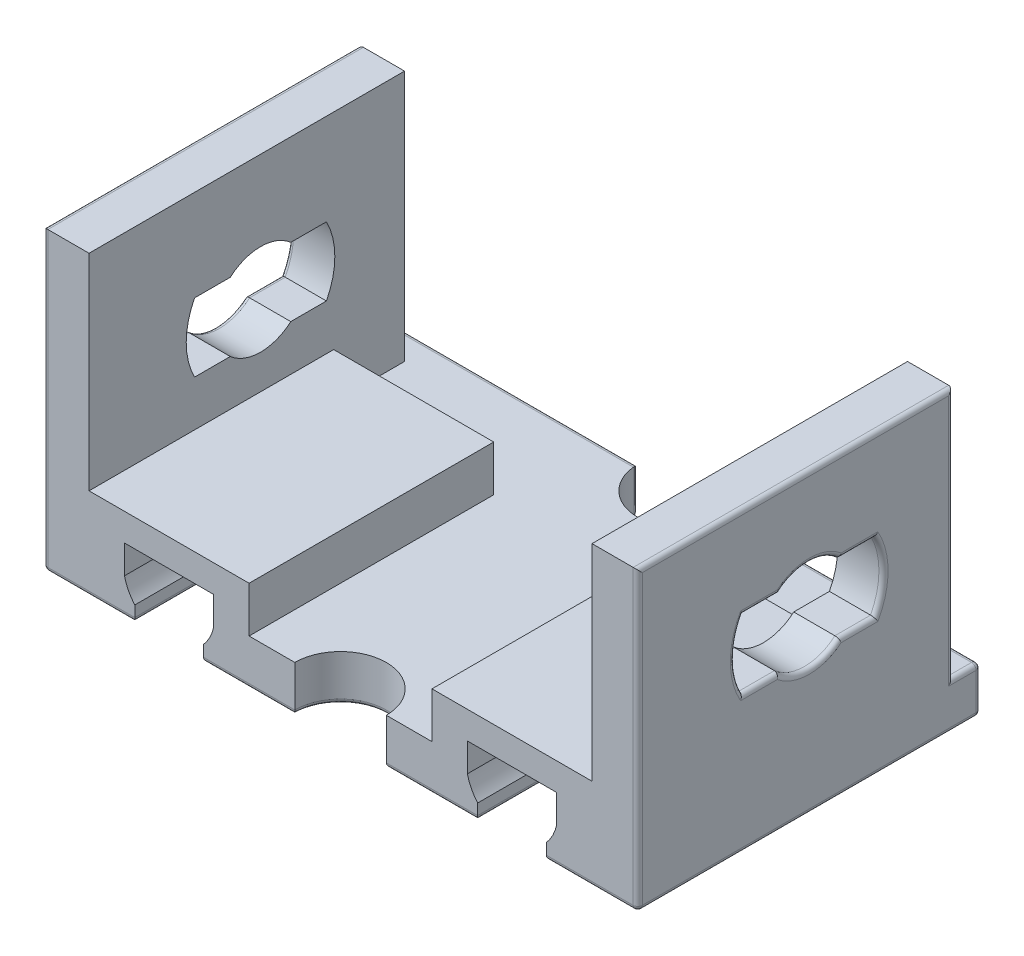
SolidWorks part; units mm, degrees
ref_plane "前视基准面" through (0, 0, 0) normal (0, 0, 1) x (1, 0, 0)
ref_plane "上视基准面" through (0, 0, 0) normal (0, 1, 0) x (1, 0, 0)
ref_plane "右视基准面" through (0, 0, 0) normal (1, 0, 0) x (0, 0, -1)
sketch "草图1" plane through (0, 0, 0) normal (0, 1, 0) x (1, 0, 0)
  line L0 (-13, 7.5) -> (-13, -7.5)
  line L1 (-13, 7.5) -> (13, 7.5)
  line L2 (-13, -7.5) -> (13, -7.5)
  line L3 (13, 7.5) -> (13, -7.5)
  line L4 (-13, 7.5) -> (13, -7.5) construction
  line L5 (-13, -7.5) -> (13, 7.5) construction
  point P1 (0, 0)
  dimension "D1" = 26
  dimension "D2" = 15
extrude "凸台-拉伸1" add sketch "草图1" along normal blind 2
sketch "草图2" plane through (0, 2, 0) normal (0, 1, 0) x (1, 0, 0)
  line L1 (-13, -7.5) -> (-11, -7.5)
  line L2 (-13, -7.5) -> (-13, 6.3)
  line L3 (-13, 6.3) -> (-11, 6.3)
  line L4 (-11, -7.5) -> (-11, 6.3)
  dimension "D1" = 13.8
  dimension "D2" = 2
extrude "凸台-拉伸2" add sketch "草图2" along normal blind 11
sketch "草图3" plane through (0, 2, 0) normal (0, 1, 0) x (1, 0, 0)
  line L1 (-11, -7.5) -> (-4, -7.5)
  line L2 (-11, -7.5) -> (-11, 3.2)
  line L3 (-11, 3.2) -> (-4, 3.2)
  line L4 (-4, -7.5) -> (-4, 3.2)
  dimension "D1" = 7
  dimension "D2" = 10.7
extrude "凸台-拉伸3" add sketch "草图3" along normal blind 2
sketch "草图4" plane through (-13, 0, 0) normal (-1, 0, 0) x (0, 0, 1)
  line L0 (0, 0) -> (0, 7.5) construction
  line L1 (-3.25, 7.5) -> (3.25, 7.5) construction
  line L2 (-2.8831, 6) -> (-1.3229, 6)
  line L3 (-2.8831, 9) -> (-1.3229, 9)
  line L4 (1.3229, 9) -> (2.8831, 9)
  line L5 (-3.25, 9) -> (3.25, 9) construction
  line L6 (-3.25, 6) -> (3.25, 6) construction
  line L7 (1.3229, 6) -> (2.8831, 6)
  arc A0 (-1.3229, 6) -> (1.3229, 6) centre (0, 7.5) ccw
  arc A1 (2.8831, 6) -> (2.8831, 9) centre (0, 7.5) ccw
  arc A2 (1.3229, 9) -> (-1.3229, 9) centre (0, 7.5) ccw
  arc A3 (-2.8831, 9) -> (-2.8831, 6) centre (0, 7.5) ccw
  dimension "D2" = 4
  dimension "D3" = 6.5
  dimension "D1" = 7.5
  dimension "D4" = 1.5
  dimension "D5" = 1.5
extrude "切除-拉伸1" cut sketch "草图4" against normal up to next
sketch "草图5" plane through (0, 0, 7.5) normal (0, 0, 1) x (1, 0, 0)
  line L0 (0, 0) -> (-7.5, 0) construction
  line L1 (-13, 0) -> (13, 0) construction
  line L2 (-7.5, 0) -> (-7.5, 2) construction
  line L3 (-7.5, 2) -> (-7.5, 2.8) construction
  line L4 (-6, 0) -> (-9, 0)
  line L5 (-9, 0) -> (-9, 0.6771)
  line L6 (-5.55, 2.8) -> (-9.45, 2.8)
  line L7 (-9.45, 2.8) -> (-9.45, 1.5556)
  line L8 (-6, 0) -> (-6, 0.6771)
  line L9 (-5.55, 2.8) -> (-5.55, 1.5556)
  arc A0 (-9.45, 1.5556) -> (-9, 0.6771) centre (-7.5, 2) ccw
  arc A1 (-5.55, 1.5556) -> (-6, 0.6771) centre (-7.5, 2) cw
  dimension "D1" = 7.5
  dimension "D2" = 2
  dimension "D3" = 0.8
  dimension "D4" = 1.5
  dimension "D5" = 1.95
extrude "切除-拉伸2" cut sketch "草图5" against normal blind 10
mirror "镜向1" about plane through (0, 0, 0) normal (1, 0, 0) of "切除-拉伸2", "切除-拉伸1", "凸台-拉伸3", "凸台-拉伸2"
sketch "草图6" plane through (0, 2, 0) normal (0, 1, 0) x (1, 0, 0)
  line L0 (-4, -7.5) -> (4, -7.5) construction
  line L1 (13, 7.5) -> (-13, 7.5) construction
  circle A0 centre (0, -7.5) radius 2
  circle A1 centre (0, 7.5) radius 2
  dimension "D1" = 4
  dimension "D2" = 4
extrude "切除-拉伸3" cut sketch "草图6" against normal up to next
fillet "圆角1" radius 0.2 46 edges at (13, 6, -2.103) (13, 7.5, -3.25) (13, 9, -2.103) (13, 9.5, 0) (13, 9, 2.103) (13, 7.5, 3.25) (13, 6, 2.103) (13, 5.5, 0) (13, 6.5, 7.5) (13, 13, 0.6) (13, 7.5, -6.3) (13, 2, -6.9) (-13, 13, 0.6) (-13, 6.5, 7.5) (-13, 7.5, 3.25) (-13, 9, 2.103) (-13, 9.5, 0) (-13, 9, -2.103) (-13, 7.5, -3.25) (-13, 6, -2.103) (-13, 5.5, 0) (-13, 6, 2.103) (13, 1, -7.5) (7.5, 2, -7.5) (2, 1, -7.5) (-2, 1, -7.5) (-13, 1, -7.5) (-7.5, 2, -7.5) (-7.5, 0, -7.5) (-13, 0, 0) (-11, 0, 7.5) (-9, 0, 2.5) (-7.5, 0, -2.5) (-6, 0, 2.5) (-4, 0, 7.5) (0, 0, 5.5) (4, 0, 7.5) (6, 0, 2.5) (7.5, 0, -2.5) (9, 0, 2.5) (11, 0, 7.5) (13, 0, 0) (7.5, 0, -7.5) (0, 0, -5.5)
